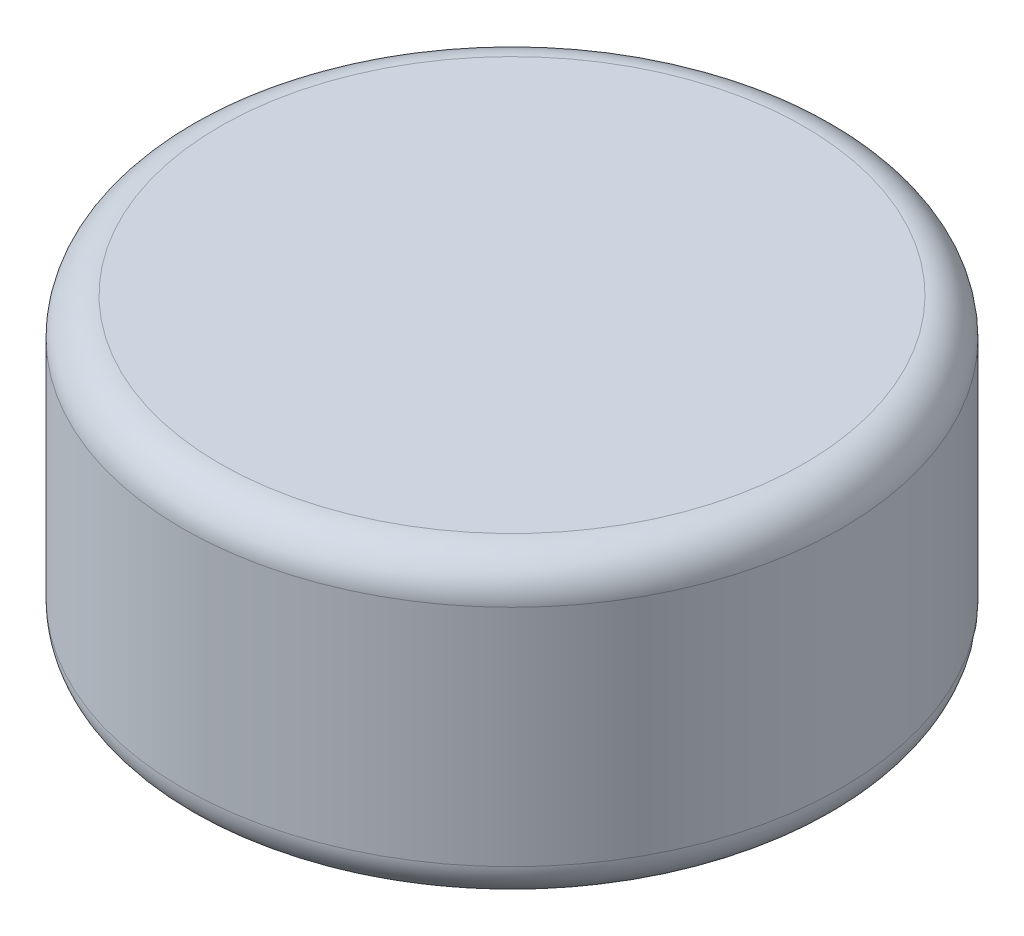
SolidWorks part; units mm, degrees
ref_plane "Front Plane" through (0, 0, 0) normal (0, 0, 1) x (1, 0, 0)
ref_plane "Top Plane" through (0, 0, 0) normal (0, 1, 0) x (1, 0, 0)
ref_plane "Right Plane" through (0, 0, 0) normal (1, 0, 0) x (0, 0, -1)
sketch "Sketch1" plane through (0, 0, 0) normal (0, 1, 0) x (1, 0, 0)
  circle A0 centre (0, 0) radius 55.88
  dimension "D1" = 111.76
extrude "Boss-Extrude1" add sketch "Sketch1" against normal blind 50.8
fillet "Fillet1" radius 6.35 2 edges at (0, -50.8, 55.88) (0, 0, 55.88)
